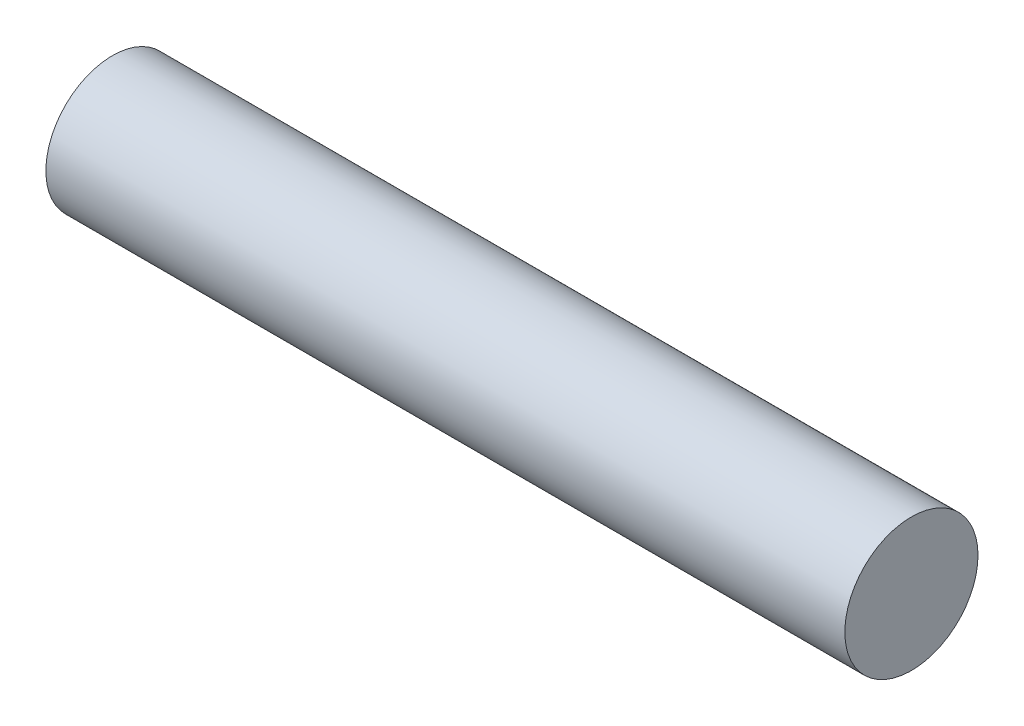
SolidWorks part; units mm, degrees
ref_plane "Plan de face" through (0, 0, 0) normal (0, 0, 1) x (1, 0, 0)
ref_plane "Plan de dessus" through (0, 0, 0) normal (0, 1, 0) x (1, 0, 0)
ref_plane "Plan de droite" through (0, 0, 0) normal (1, 0, 0) x (0, 0, -1)
sketch "Esquisse1" plane through (0, 0, 0) normal (1, 0, 0) x (0, 0, -1)
  circle A0 centre (0, 0) radius 1
  dimension "D1" = 2
extrude "Boss.-Extru.1" add sketch "Esquisse1" along normal blind 12
